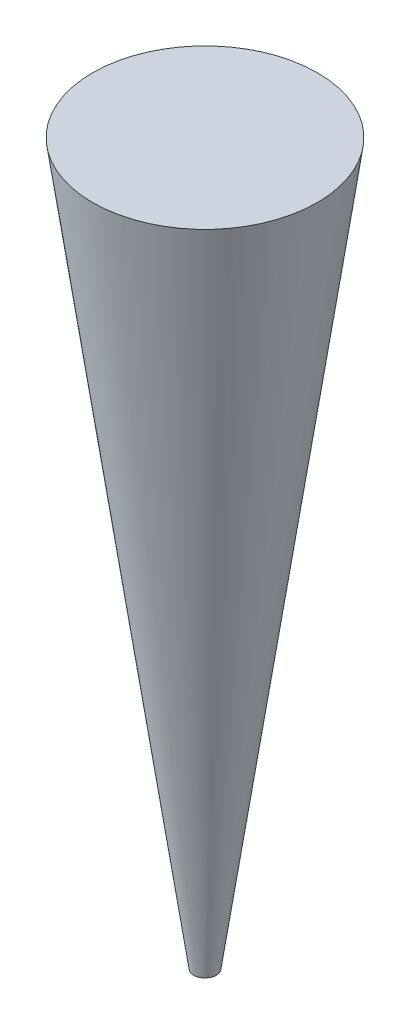
SolidWorks part; units mm, degrees
ref_plane "Front Plane" through (0, 0, 0) normal (0, 0, 1) x (1, 0, 0)
ref_plane "Top Plane" through (0, 0, 0) normal (0, 1, 0) x (1, 0, 0)
ref_plane "Right Plane" through (0, 0, 0) normal (1, 0, 0) x (0, 0, -1)
sketch "Sketch1" plane through (0, 0, 0) normal (0, 0, 1) x (1, 0, 0)
  line L0 (0, 0) -> (0, 300)
  line L1 (0, -55) -> (0, 55) construction
  line L2 (0, 0) -> (42.1623, 300)
  line L3 (42.1623, 300) -> (0, 300)
  dimension "D1" = 300
  dimension "D2" = 8
revolve "Revolve1" add sketch "Sketch1" angle 360 about L0
sketch "Sketch2" plane through (0, 0, 0) normal (0, 0, 1) x (1, 0, 0)
  line L0 (58.1879, 0) -> (-58.1879, 0) construction
  line L1 (-10.1498, 30) -> (7.9681, 30)
  line L2 (-10.1498, 30) -> (-10.1498, 0)
  line L3 (-10.1498, 0) -> (7.9681, 0)
  line L4 (7.9681, 30) -> (7.9681, 0)
  dimension "D1" = 30
extrude "Cut-Extrude1" cut sketch "Sketch2" against normal through all both and the other way through all
